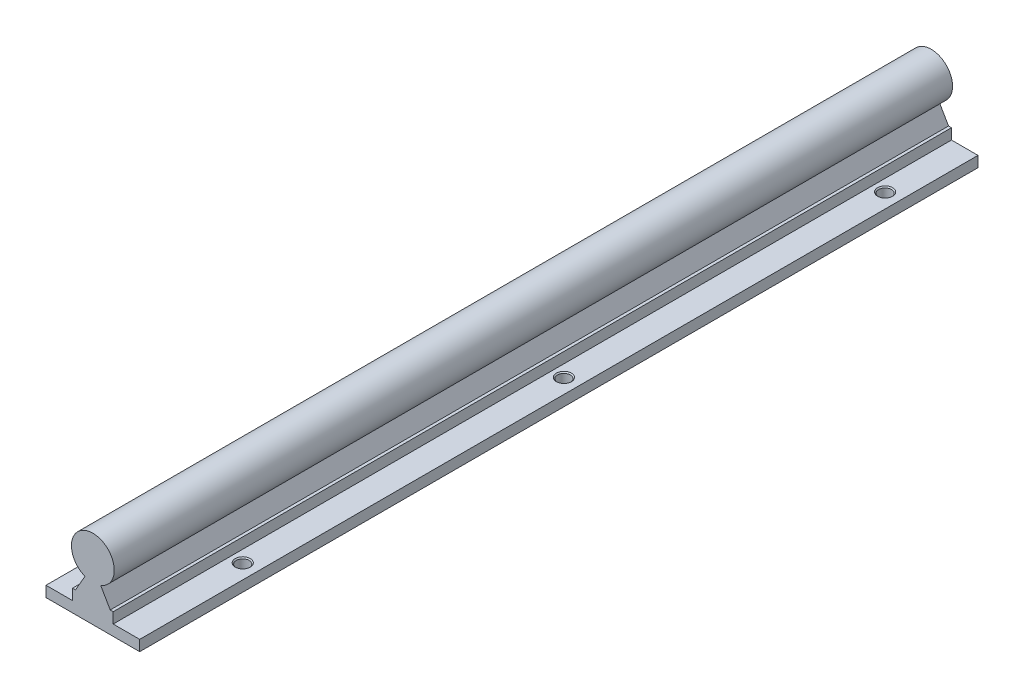
SolidWorks part; units mm, degrees
ref_plane "Alzado" through (0, 0, 0) normal (0, 0, 1) x (1, 0, 0)
ref_plane "Planta" through (0, 0, 0) normal (0, 1, 0) x (1, 0, 0)
ref_plane "Vista lateral" through (0, 0, 0) normal (1, 0, 0) x (0, 0, -1)
sketch "Croquis1" plane through (0, 0, 0) normal (0, 0, 1) x (1, 0, 0)
  line L0 (0, 0) -> (0, 27) construction
  line L1 (-8.1212, 10) -> (-3.6756, 17.7)
  line L2 (-8.1212, 10) -> (-9.5, 10)
  line L3 (-9.5, 10) -> (-9.5, 5)
  line L4 (-9.5, 5) -> (-21.88, 5)
  line L5 (-21.88, 5) -> (-21.88, 0)
  line L6 (-21.88, 0) -> (21.88, 0)
  line L7 (21.88, 5) -> (21.88, 0)
  line L8 (9.5, 5) -> (21.88, 5)
  line L9 (9.5, 10) -> (9.5, 5)
  line L10 (8.1212, 10) -> (9.5, 10)
  line L11 (8.1212, 10) -> (3.6756, 17.7)
  arc A0 (3.6756, 17.7) -> (-3.6756, 17.7) centre (0, 27) ccw
  dimension "D1" = 20
  dimension "D2" = 27
  dimension "D3" = 43.76
  dimension "D4" = 5
  dimension "D5" = 30
  dimension "D6" = 10
  dimension "D7" = 19
  dimension "D8" = 17.7
extrude "Saliente-Extruir1" add sketch "Croquis1" along normal mid plane 410
sketch "Croquis2" plane through (0, 0, 0) normal (0, -1, 0) x (1, 0, 0)
  line L0 (0, 218.8513) -> (0, -218.8513) construction
  line L1 (-21.88, 205) -> (21.88, 205) construction
  circle A0 centre (15, 150) radius 3
  circle A1 centre (-15, 150) radius 3
  circle A2 centre (-15, 0) radius 3
  circle A3 centre (15, 0) radius 3
  circle A6 centre (15, -150) radius 3
  circle A7 centre (-15, -150) radius 3
  point P4 (0, 0)
  dimension "D1" = 6
  dimension "D2" = 55
  dimension "D3" = 150
  dimension "D4" = 30
  dimension "D5" = 30
  dimension "D6" = 150
extrude "Cortar-Extruir1" cut sketch "Croquis2" against normal up to next
chamfer "Chaflán1" distance 0.5 angle 45 6 edges at (-12, 5, 150) (-12, 5, 0) (-12, 5, -150) (18, 5, -150) (18, 5, 0) (18, 5, 150)
sketch "Croquis3" plane through (0, 0, 0) normal (0, -1, 0) x (1, 0, 0)
  line L0 (21.88, 205) -> (21.88, -205) construction
  line L1 (-21.88, -205) -> (21.88, -205)
  line L2 (-21.88, -205) -> (-21.88, -186.5)
  line L3 (-21.88, -186.5) -> (21.88, -186.5)
  line L4 (21.88, -205) -> (21.88, -186.5)
  dimension "D1" = 18.5
extrude "Cortar-Extruir2" cut sketch "Croquis3" against normal through all
